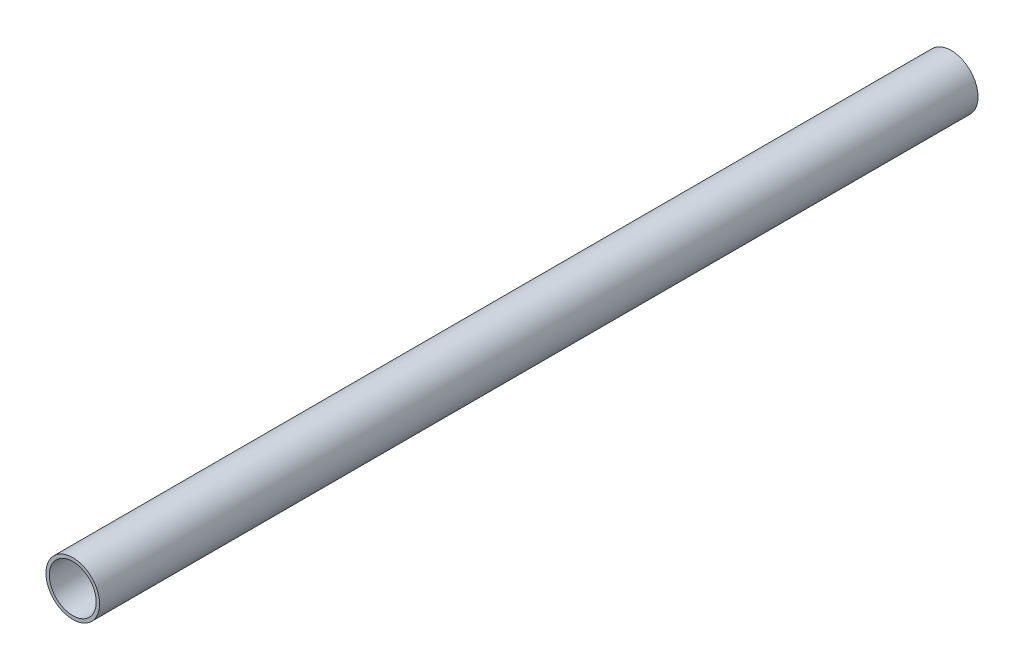
SolidWorks part; units mm, degrees
material "Thornel Mat VMA"
ref_plane "Front Plane" through (0, 0, 0) normal (0, 0, 1) x (1, 0, 0)
ref_plane "Top Plane" through (0, 0, 0) normal (0, 1, 0) x (1, 0, 0)
ref_plane "Right Plane" through (0, 0, 0) normal (1, 0, 0) x (0, 0, -1)
sketch "Sketch1" plane through (0, 0, 0) normal (0, 0, 1) x (1, 0, 0)
  circle A0 centre (0, 0) radius 8
ref_plane "Plane1" through (0, 0, 262) normal (0, 0, 1) x (1, 0, 0)
sketch "Sketch2" plane through (0, 0, 262) normal (0, 0, 1) x (1, 0, 0)
  circle A0 centre (0, 0) radius 8
sketch "Sketch3" plane through (0, 0, 0) normal (0, 0, 1) x (1, 0, 0)
  circle A0 centre (0, 0) radius 7
loft "Loft3" add profiles "Sketch1", "Sketch2"
extrude "Cut-Extrude2" cut sketch "Sketch3" against normal through all both and the other way through all
